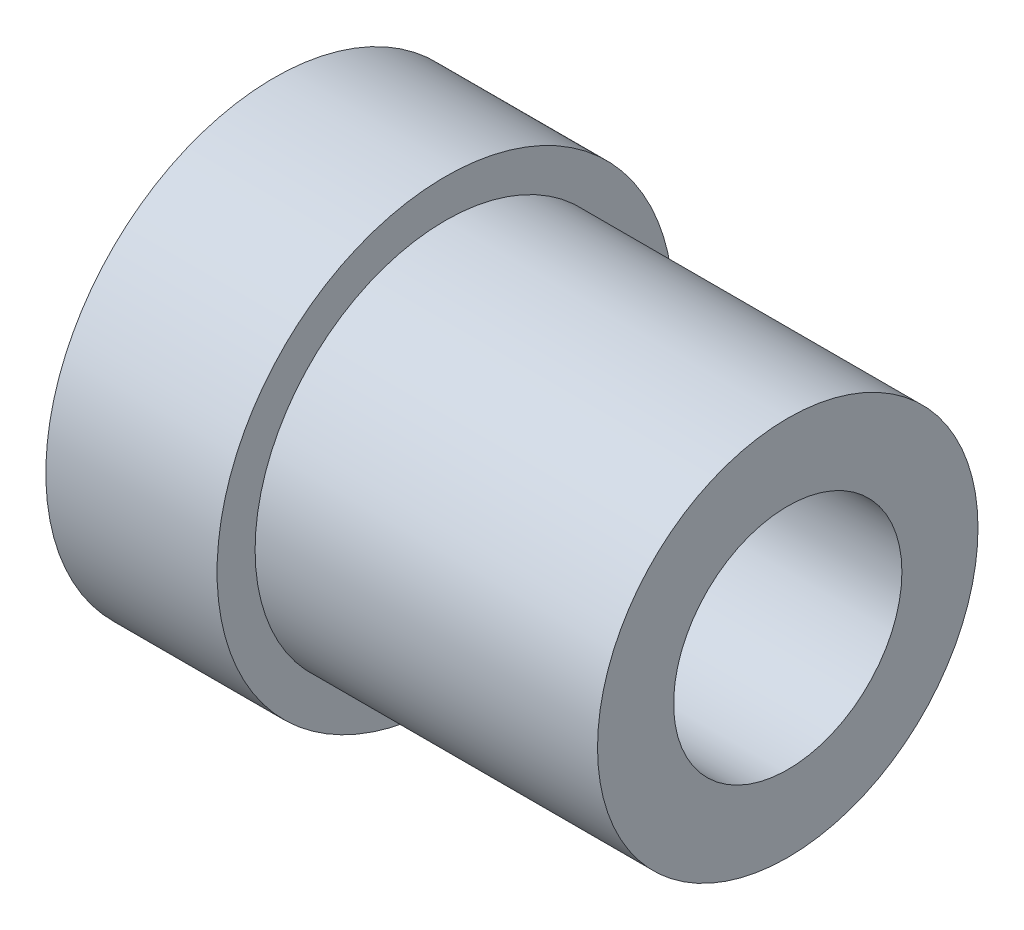
SolidWorks part; units mm, degrees
ref_plane "Front Plane" through (0, 0, 0) normal (0, 0, 1) x (1, 0, 0)
ref_plane "Top Plane" through (0, 0, 0) normal (0, 1, 0) x (1, 0, 0)
ref_plane "Right Plane" through (0, 0, 0) normal (1, 0, 0) x (0, 0, -1)
sketch "Sketch1" plane through (0, 0, 0) normal (1, 0, 0) x (0, 0, -1)
  circle A0 centre (0, 0) radius 6
  circle A1 centre (0, 0) radius 3
  dimension "D1" = 12
  dimension "D2" = 6
extrude "Boss-Extrude1" add sketch "Sketch1" along normal blind 4.5
sketch "Sketch2" plane through (4.5, 0, 0) normal (1, 0, 0) x (0, 0, -1)
  circle A0 centre (0, 0) radius 3
  circle A1 centre (0, 0) radius 5
  dimension "D1" = 10
extrude "Boss-Extrude2" add sketch "Sketch2" along normal blind 9
